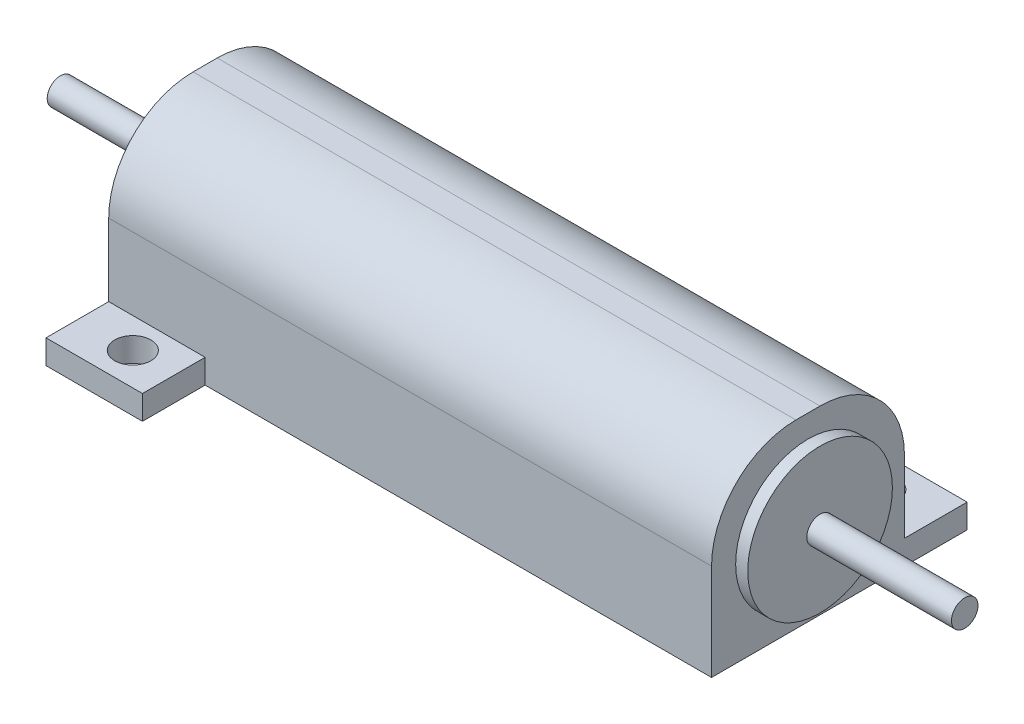
SolidWorks part; units mm, degrees
ref_plane "Спереди" through (0, 0, 0) normal (0, 0, 1) x (1, 0, 0)
ref_plane "Сверху" through (0, 0, 0) normal (0, 1, 0) x (1, 0, 0)
ref_plane "Справа" through (0, 0, 0) normal (1, 0, 0) x (0, 0, -1)
other "Configuration Table"
sketch "Эскиз1" plane through (0, 0, 0) normal (0, 1, 0) x (1, 0, 0)
  line L1 (0, 0) -> (50, 0)
  line L2 (0, 0) -> (0, -16)
  line L3 (0, -16) -> (50, -16)
  line L4 (50, 0) -> (50, -16)
  dimension "D1" = 50
  dimension "D2" = 16
extrude "Бобышка-Вытянуть1" add sketch "Эскиз1" along normal blind 15
sketch "Эскиз2" plane through (0, 0, 0) normal (0, -1, 0) x (1, 0, 0)
  line L1 (0, 16) -> (8, 16)
  line L2 (0, 16) -> (0, 21.2)
  line L3 (0, 21.2) -> (8, 21.2)
  line L4 (8, 16) -> (8, 21.2)
  line L5 (50, 0) -> (42, 0)
  line L6 (50, 0) -> (50, -5.2)
  line L7 (50, -5.2) -> (42, -5.2)
  line L8 (42, 0) -> (42, -5.2)
  circle A0 centre (4.5, 18.5) radius 1.5
  circle A1 centre (45.5, -2.5) radius 1.5
  dimension "D5" = 3
  dimension "D6" = 3
  dimension "D1" = 8
  dimension "D2" = 5.2
  dimension "D3" = 5.2
  dimension "D4" = 8
  dimension "D7" = 4.5
  dimension "D8" = 2.5
  dimension "D9" = 2.5
  dimension "D10" = 4.5
  dimension "D11" = 41
  dimension "D12" = 21
extrude "Бобышка-Вытянуть2" add sketch "Эскиз2" against normal blind 2
fillet "Скругление1" radius 7 2 edges at (25, 15, 16) (25, 15, 0)
sketch "Эскиз3" plane through (50, 0, 0) normal (1, 0, 0) x (0, 0, -1)
  line L0 (-16, 8) -> (-16, 0) construction
  circle A0 centre (-8, 7.1282) radius 6
  dimension "D1" = 12
  dimension "D2" = 8
extrude "Бобышка-Вытянуть3" add sketch "Эскиз3" along normal blind 1 and the other way blind 51
sketch "Эскиз4" plane through (51, 0, 0) normal (1, 0, 0) x (0, 0, -1)
  circle A0 centre (-8, 7.1282) radius 1.1
  dimension "D1" = 2.2
extrude "Бобышка-Вытянуть4" add sketch "Эскиз4" along normal blind 12 and the other way blind 63
